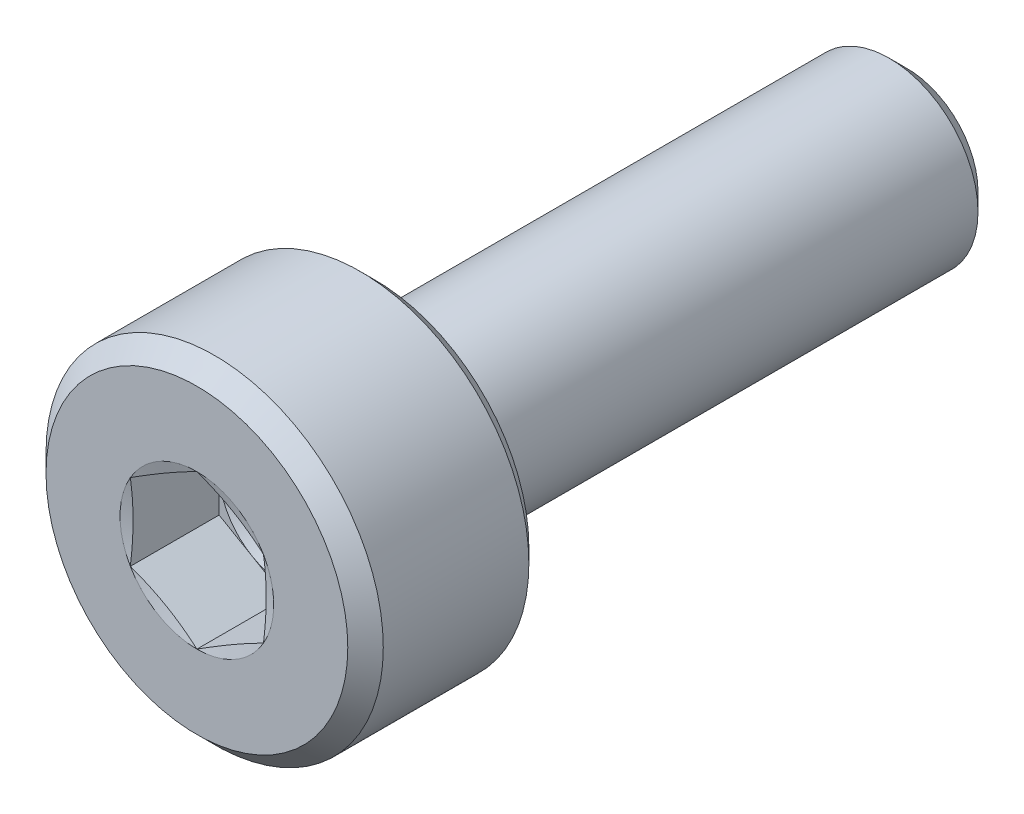
SolidWorks part; units mm, degrees
ref_plane "Front Plane" through (0, 0, 0) normal (0, 0, 1) x (1, 0, 0)
ref_plane "Top Plane" through (0, 0, 0) normal (0, 1, 0) x (1, 0, 0)
ref_plane "Right Plane" through (0, 0, 0) normal (1, 0, 0) x (0, 0, -1)
sketch "Sketch1" plane through (0, 0, 0) normal (1, 0, 0) x (0, 0, -1)
  line L0 (0, 0) -> (12.9407, 0) construction
  line L1 (0, 0) -> (0, 1.7)
  line L2 (0, 1.7) -> (0.2, 1.9)
  line L3 (0.2, 1.9) -> (1.84, 1.9)
  line L4 (2, 1.74) -> (2, 1.3)
  line L5 (2.51, 1) -> (7.8, 1)
  line L6 (7.8, 1) -> (8, 0.8)
  line L7 (8, 0.8) -> (8, 0)
  line L8 (8, 0) -> (0, 0)
  line L9 (1.84, 1.9) -> (2, 1.74)
  line L10 (2.4662, 1.0101) -> (2.0562, 1.2101)
  arc A2 (2.51, 1) -> (2.4662, 1.0101) centre (2.51, 1.1) cw
  arc A3 (2.0562, 1.2101) -> (2, 1.3) centre (2.1, 1.3) cw
  point P6 (2, 1.9)
  dimension "R2" = 0.1
  dimension "R1" = 0.1
  dimension "D1" = 45
  dimension "DK" = 3.8
  dimension "D3" = 45
  dimension "length" = 6
  dimension "K" = 2
  dimension "V" = 0.2
  dimension "HOLESIZE" = 2
  dimension "D4" = 1.6
  dimension "D5" = 45
  dimension "DW" = 3.48
  dimension "F" = 0.51
  dimension "DA" = 2.6
revolve "Revolve1" add sketch "Sketch1" angle 360 about L0
cosmetic thread "Cosmetic Thread1" parameters "D1"=4.8, "D2"=2
sketch "Sketch2" plane through (0, 0, 0) normal (0, 0, 1) x (1, 0, 0)
  line L0 (0, 0) -> (0, 0.866) construction
  line L2 (0, 0.866) -> (-0.75, 0.433)
  line L3 (-0.75, 0.433) -> (-0.75, -0.433)
  line L4 (-0.75, -0.433) -> (0, -0.866)
  line L5 (0, -0.866) -> (0.75, -0.433)
  line L6 (0.75, -0.433) -> (0.75, 0.433)
  line L7 (0.75, 0.433) -> (0, 0.866)
  circle A0 centre (0, 0) radius 0.75 construction
  dimension "S" = 1.5
extrude "Cut-Extrude1" cut sketch "Sketch2" against normal blind 1
sketch "Sketch3" plane through (0, 0, 0) normal (1, 0, 0) x (0, 0, -1)
  line L0 (1, 0) -> (8, 0) construction
  line L1 (8, -0.8) -> (8, 0.8) construction
  line L2 (1, 0) -> (1, 0.75)
  line L4 (1, 0.75) -> (1.433, 0)
  line L5 (1.433, 0) -> (1, 0)
  line L6 (0, 1.7) -> (0, -1.7) construction
  dimension "DRILLANG" = 60
  dimension "DRILL DEPTH" = 1
  dimension "S2" = 1.5
revolve "Cut-Revolve2" cut sketch "Sketch3" angle 360 about L0
sketch "Sketch4" plane through (0, 0, 0) normal (1, 0, 0) x (0, 0, -1)
  line L0 (0, 0) -> (4.6121, 0) construction
  line L1 (0, 0.866) -> (0, 0.75)
  line L2 (0, 1.7) -> (0, -1.7) construction
  line L3 (0, 0.75) -> (0.0311, 0.75)
  line L4 (0.0311, 0.75) -> (0, 0.866)
  point P12 (0.0155, 0.75)
  dimension "D1" = 1.5
  dimension "D2" = 15
revolve "Cut-Revolve3" cut sketch "Sketch4" angle 360 about L0
